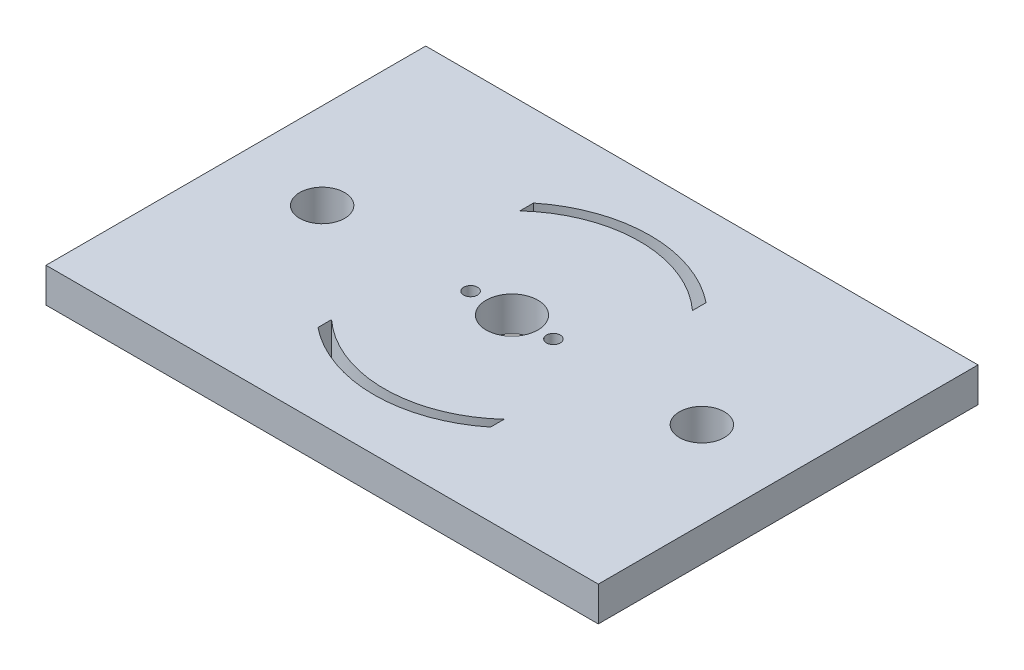
SolidWorks part; units mm, degrees
ref_plane "Front Plane" through (0, 0, 0) normal (0, 0, 1) x (1, 0, 0)
ref_plane "Top Plane" through (0, 0, 0) normal (0, 1, 0) x (1, 0, 0)
ref_plane "Right Plane" through (0, 0, 0) normal (1, 0, 0) x (0, 0, -1)
sketch "Sketch1" plane through (0, 0, 0) normal (0, 1, 0) x (1, 0, 0)
  line L0 (-25, 31.225) -> (-25, 27.2764)
  line L1 (-80, 55) -> (80, 55)
  line L2 (-80, 55) -> (-80, -55)
  line L3 (-80, -55) -> (80, -55)
  line L4 (80, 55) -> (80, -55)
  line L5 (-80, 55) -> (80, -55) construction
  line L6 (-80, -55) -> (80, 55) construction
  line L7 (0, 55) -> (0, -55) construction
  line L8 (25, 31.225) -> (25, 27.2764)
  line L9 (-25, -27.2764) -> (-25, -31.225)
  line L10 (25, -27.2764) -> (25, -31.225)
  circle A0 centre (-55, 0) radius 6.5
  arc A1 (-25, -31.225) -> (25, -31.225) centre (0, 0) ccw
  arc A2 (-25, -27.2764) -> (25, -27.2764) centre (0, 0) ccw
  circle A5 centre (55, 0) radius 6.5
  circle A6 centre (0, 0) radius 37 construction
  circle A7 centre (0, 0) radius 40 construction
  arc A8 (25, 27.2764) -> (-25, 27.2764) centre (0, 0) ccw
  arc A9 (25, 31.225) -> (-25, 31.225) centre (0, 0) ccw
  circle A10 centre (0, 0) radius 7.5
  point P0 (0, 0)
  dimension "D1" = 13
  dimension "D4" = 80
  dimension "D9" = 15
  dimension "D2" = 55
  dimension "D3" = 160
  dimension "D6" = 25
  dimension "D7" = 110
  dimension "D8" = 25
  dimension "D5" = 3
extrude "Boss-Extrude1" add sketch "Sketch1" along normal blind 10
sketch "Sketch2" plane through (0, 10, 0) normal (0, 1, 0) x (1, 0, 0)
  line L0 (0, 7.5) -> (0, -7.5) construction
  circle A0 centre (-12, 0) radius 2
  circle A1 centre (0, 0) radius 7.5 construction
  circle A2 centre (12, 0) radius 2
  dimension "D1" = 4
  dimension "D2" = 12
extrude "Cut-Extrude1" cut sketch "Sketch2" against normal blind 5
